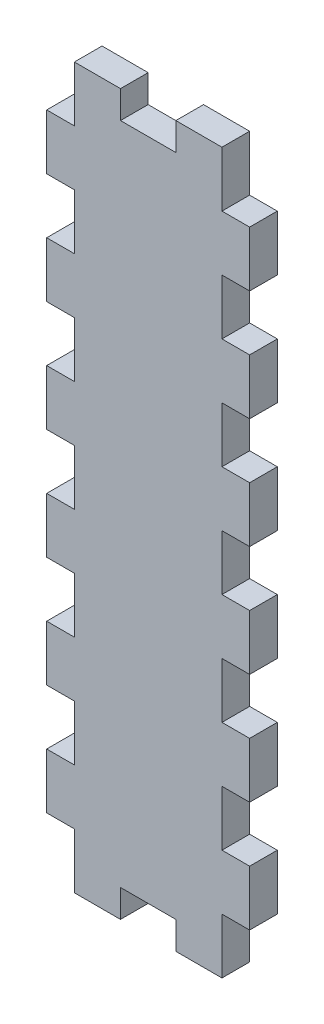
SolidWorks part; units mm, degrees
material "PMMA"
ref_plane "前视基准面" through (0, 0, 0) normal (0, 0, 1) x (1, 0, 0)
ref_plane "上视基准面" through (0, 0, 0) normal (0, 1, 0) x (1, 0, 0)
ref_plane "右视基准面" through (0, 0, 0) normal (1, 0, 0) x (0, 0, -1)
other "Configuration Table"
sketch "草图2" plane through (0, 0, 0) normal (0, 0, 1) x (1, 0, 0)
  line L0 (67, 81) -> (67, 75)
  line L1 (67, 75) -> (64, 75)
  line L2 (64, 75) -> (64, 69)
  line L3 (64, 69) -> (67, 69)
  line L4 (67, 69) -> (67, 63)
  line L5 (67, 63) -> (64, 63)
  line L6 (64, 63) -> (64, 57)
  line L7 (64, 57) -> (67, 57)
  line L8 (67, 57) -> (67, 51)
  line L9 (67, 51) -> (64, 51)
  line L10 (64, 51) -> (64, 45)
  line L11 (64, 45) -> (67, 45)
  line L12 (67, 45) -> (67, 39)
  line L13 (67, 39) -> (64, 39)
  line L14 (64, 39) -> (64, 33)
  line L15 (64, 33) -> (67, 33)
  line L16 (67, 33) -> (67, 27)
  line L17 (67, 27) -> (64, 27)
  line L18 (64, 27) -> (64, 21)
  line L19 (64, 21) -> (67, 21)
  line L20 (67, 21) -> (67, 15)
  line L21 (67, 15) -> (64, 15)
  line L22 (64, 15) -> (64, 9)
  line L23 (64, 9) -> (67, 9)
  line L24 (67, 9) -> (67, 3)
  line L25 (67, 3) -> (72, 3)
  line L26 (72, 3) -> (72, 6)
  line L27 (72, 6) -> (78, 6)
  line L28 (78, 6) -> (78, 3)
  line L29 (78, 3) -> (83, 3)
  line L30 (83, 3) -> (83, 9)
  line L31 (83, 9) -> (86, 9)
  line L32 (86, 9) -> (86, 15)
  line L33 (86, 15) -> (83, 15)
  line L34 (83, 15) -> (83, 21)
  line L35 (83, 21) -> (86, 21)
  line L36 (86, 21) -> (86, 27)
  line L37 (86, 27) -> (83, 27)
  line L38 (83, 27) -> (83, 33)
  line L39 (83, 33) -> (86, 33)
  line L40 (86, 33) -> (86, 39)
  line L41 (86, 39) -> (83, 39)
  line L42 (83, 39) -> (83, 45)
  line L43 (83, 45) -> (86, 45)
  line L44 (86, 45) -> (86, 51)
  line L45 (86, 51) -> (83, 51)
  line L46 (83, 51) -> (83, 57)
  line L47 (83, 57) -> (86, 57)
  line L48 (86, 57) -> (86, 63)
  line L49 (86, 63) -> (83, 63)
  line L50 (83, 63) -> (83, 69)
  line L51 (83, 69) -> (86, 69)
  line L52 (86, 69) -> (86, 75)
  line L53 (86, 75) -> (83, 75)
  line L54 (83, 75) -> (83, 81)
  line L55 (83, 81) -> (78, 81)
  line L56 (78, 81) -> (78, 78)
  line L57 (78, 78) -> (72, 78)
  line L58 (72, 78) -> (72, 81)
  line L59 (72, 81) -> (67, 81)
extrude "凸台-拉伸1" add sketch "草图2" along normal blind 3
